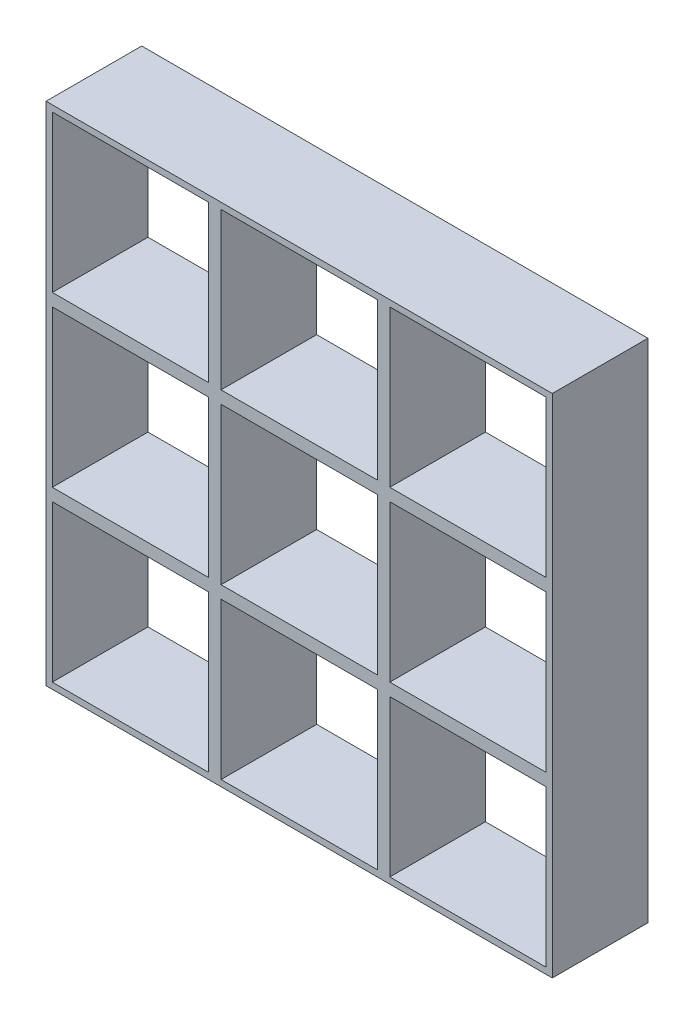
SolidWorks part; units mm, degrees
material "Acrylic (Medium-high impact)"
ref_plane "Front Plane" through (0, 0, 0) normal (0, 0, 1) x (1, 0, 0)
ref_plane "Top Plane" through (0, 0, 0) normal (0, 1, 0) x (1, 0, 0)
ref_plane "Right Plane" through (0, 0, 0) normal (1, 0, 0) x (0, 0, -1)
sketch "Sketch1" plane through (0, 0, 0) normal (0, 0, 1) x (1, 0, 0)
  line L0 (-497.3379, -371.0922) -> (-497.3379, -871.0922)
  line L1 (-1017.3379, 728.9078) -> (602.6621, 728.9078)
  line L2 (-1017.3379, 728.9078) -> (-1017.3379, -891.0922)
  line L3 (-1017.3379, -891.0922) -> (602.6621, -891.0922)
  line L4 (602.6621, 728.9078) -> (602.6621, -891.0922)
  line L5 (42.6621, -371.0922) -> (42.6621, -871.0922)
  line L6 (-997.3379, 168.9078) -> (-997.3379, -331.0922)
  line L7 (82.6621, 168.9078) -> (582.6621, 168.9078)
  line L8 (-497.3379, 708.9078) -> (-497.3379, 208.9078)
  line L9 (42.6621, 708.9078) -> (42.6621, 208.9078)
  line L10 (-997.3379, 168.9078) -> (-497.3379, 168.9078)
  line L11 (-997.3379, 708.9078) -> (-497.3379, 708.9078)
  line L12 (582.6621, 708.9078) -> (582.6621, 208.9078)
  line L13 (-997.3379, -371.0922) -> (-497.3379, -371.0922)
  line L14 (-997.3379, 708.9078) -> (-997.3379, 208.9078)
  line L15 (-997.3379, -871.0922) -> (-497.3379, -871.0922)
  line L16 (82.6621, 708.9078) -> (82.6621, 208.9078)
  line L17 (-457.3379, 708.9078) -> (-457.3379, 208.9078)
  line L18 (-997.3379, -331.0922) -> (-497.3379, -331.0922)
  line L19 (-997.3379, 208.9078) -> (-497.3379, 208.9078)
  line L20 (-1017.3379, 708.9078) -> (582.6621, 708.9078) construction
  line L21 (-997.3379, 728.9078) -> (-997.3379, -871.0922) construction
  line L22 (-457.3379, -331.0922) -> (42.6621, -331.0922)
  line L23 (-457.3379, 708.9078) -> (42.6621, 708.9078)
  line L24 (82.6621, -331.0922) -> (582.6621, -331.0922)
  line L25 (82.6621, -871.0922) -> (582.6621, -871.0922)
  line L28 (82.6621, 708.9078) -> (582.6621, 708.9078)
  line L30 (-457.3379, 208.9078) -> (42.6621, 208.9078)
  line L31 (582.6621, -371.0922) -> (582.6621, -871.0922)
  line L33 (-457.3379, -371.0922) -> (-457.3379, -871.0922)
  line L34 (-457.3379, 168.9078) -> (42.6621, 168.9078)
  line L35 (-457.3379, -871.0922) -> (42.6621, -871.0922)
  line L36 (-997.3379, -371.0922) -> (-997.3379, -871.0922)
  line L37 (-457.3379, 168.9078) -> (-457.3379, -331.0922)
  line L38 (-497.3379, 168.9078) -> (-497.3379, -331.0922)
  line L39 (-457.3379, -371.0922) -> (42.6621, -371.0922)
  line L40 (82.6621, -371.0922) -> (82.6621, -871.0922)
  line L41 (-997.3379, -871.0922) -> (602.6621, -871.0922) construction
  line L42 (82.6621, 208.9078) -> (582.6621, 208.9078)
  line L44 (82.6621, -371.0922) -> (582.6621, -371.0922)
  line L45 (582.6621, 708.9078) -> (582.6621, -891.0922) construction
  line L46 (582.6621, 168.9078) -> (582.6621, -331.0922)
  line L47 (42.6621, 168.9078) -> (42.6621, -331.0922)
  line L48 (82.6621, 168.9078) -> (82.6621, -331.0922)
  dimension "D1" = 1620
  dimension "D2" = 1620
  dimension "D7" = 20
  dimension "D8" = 20
extrude "Boss-Extrude1" add sketch "Sketch1" along normal blind 300
sketch "Sketch2" plane through (0, 0, 300) normal (0, 0, 1) x (1, 0, 0)
  line L1 (-1017.3379, 728.9078) -> (602.6621, 728.9078)
  line L2 (-1017.3379, 728.9078) -> (-1017.3379, -891.0922)
  line L3 (-1017.3379, -891.0922) -> (602.6621, -891.0922)
  line L4 (602.6621, 728.9078) -> (602.6621, -891.0922)
  line L5 (82.6621, 708.9078) -> (582.6621, 708.9078)
  line L6 (-997.3379, 708.9078) -> (-497.3379, 708.9078)
  line L7 (-997.3379, 708.9078) -> (-997.3379, 208.9078)
  line L8 (-997.3379, 208.9078) -> (-497.3379, 208.9078)
  line L9 (-497.3379, 708.9078) -> (-497.3379, 208.9078)
  line L10 (-457.3379, 708.9078) -> (42.6621, 708.9078)
  line L11 (-457.3379, 708.9078) -> (-457.3379, 208.9078)
  line L12 (-457.3379, 208.9078) -> (42.6621, 208.9078)
  line L13 (42.6621, 708.9078) -> (42.6621, 208.9078)
  line L14 (82.6621, 708.9078) -> (82.6621, 208.9078)
  line L15 (82.6621, 208.9078) -> (582.6621, 208.9078)
  line L16 (582.6621, 708.9078) -> (582.6621, 208.9078)
  line L18 (-997.3379, 168.9078) -> (-497.3379, 168.9078)
  line L19 (-997.3379, 168.9078) -> (-997.3379, -331.0922)
  line L20 (-997.3379, -331.0922) -> (-497.3379, -331.0922)
  line L21 (-497.3379, 168.9078) -> (-497.3379, -331.0922)
  line L22 (-457.3379, 168.9078) -> (42.6621, 168.9078)
  line L23 (-457.3379, 168.9078) -> (-457.3379, -331.0922)
  line L24 (-457.3379, -331.0922) -> (42.6621, -331.0922)
  line L25 (42.6621, 168.9078) -> (42.6621, -331.0922)
  line L26 (82.6621, 168.9078) -> (582.6621, 168.9078)
  line L27 (82.6621, 168.9078) -> (82.6621, -331.0922)
  line L28 (82.6621, -331.0922) -> (582.6621, -331.0922)
  line L29 (582.6621, 168.9078) -> (582.6621, -331.0922)
  line L33 (-997.3379, -371.0922) -> (-497.3379, -371.0922)
  line L34 (-997.3379, -371.0922) -> (-997.3379, -871.0922)
  line L35 (-997.3379, -871.0922) -> (-497.3379, -871.0922)
  line L36 (-497.3379, -371.0922) -> (-497.3379, -871.0922)
  line L37 (-457.3379, -371.0922) -> (42.6621, -371.0922)
  line L38 (-457.3379, -371.0922) -> (-457.3379, -871.0922)
  line L39 (-457.3379, -871.0922) -> (42.6621, -871.0922)
  line L40 (42.6621, -371.0922) -> (42.6621, -871.0922)
  line L42 (82.6621, -371.0922) -> (582.6621, -371.0922)
  line L43 (82.6621, -371.0922) -> (82.6621, -871.0922)
  line L44 (82.6621, -871.0922) -> (582.6621, -871.0922)
  line L45 (582.6621, -371.0922) -> (582.6621, -871.0922)
extrude "Boss-Extrude2" add sketch "Sketch2" along normal blind 3
sketch "Sketch3" plane through (0, 0, 0) normal (0, 0, -1) x (-1, 0, 0)
  line L0 (997.3379, -871.0922) -> (497.3379, -871.0922) construction
  line L1 (-602.6621, 728.9078) -> (1017.3379, 728.9078)
  line L2 (-602.6621, 728.9078) -> (-602.6621, -891.0922)
  line L3 (-602.6621, -891.0922) -> (1017.3379, -891.0922)
  line L4 (1017.3379, 728.9078) -> (1017.3379, -891.0922)
  line L5 (497.3379, -371.0922) -> (997.3379, -371.0922)
  line L6 (497.3379, -371.0922) -> (497.3379, -871.0922)
  line L7 (497.3379, -871.0922) -> (997.3379, -871.0922)
  line L8 (997.3379, -371.0922) -> (997.3379, -871.0922)
  line L9 (997.3379, -371.0922) -> (997.3379, -871.0922) construction
  line L11 (457.3379, -871.0922) -> (-42.6621, -871.0922)
  line L12 (457.3379, -871.0922) -> (457.3379, -371.0922)
  line L13 (457.3379, -371.0922) -> (-42.6621, -371.0922)
  line L14 (-42.6621, -871.0922) -> (-42.6621, -371.0922)
  line L15 (-82.6621, -371.0922) -> (-582.6621, -371.0922)
  line L16 (-82.6621, -371.0922) -> (-82.6621, -871.0922)
  line L17 (-82.6621, -871.0922) -> (-582.6621, -871.0922)
  line L18 (-582.6621, -371.0922) -> (-582.6621, -871.0922)
  line L19 (-42.6621, 168.9078) -> (457.3379, 168.9078)
  line L20 (-582.6621, -331.0922) -> (-82.6621, -331.0922)
  line L21 (-582.6621, -331.0922) -> (-582.6621, 168.9078)
  line L22 (-582.6621, 168.9078) -> (-82.6621, 168.9078)
  line L23 (-82.6621, -331.0922) -> (-82.6621, 168.9078)
  line L24 (-42.6621, 168.9078) -> (-42.6621, -331.0922)
  line L25 (-42.6621, -331.0922) -> (457.3379, -331.0922)
  line L26 (457.3379, 168.9078) -> (457.3379, -331.0922)
  line L27 (457.3379, 708.9078) -> (-42.6621, 708.9078)
  line L28 (497.3379, -331.0922) -> (997.3379, -331.0922)
  line L29 (497.3379, -331.0922) -> (497.3379, 168.9078)
  line L30 (497.3379, 168.9078) -> (997.3379, 168.9078)
  line L31 (997.3379, -331.0922) -> (997.3379, 168.9078)
  line L32 (997.3379, 208.9078) -> (497.3379, 208.9078)
  line L33 (997.3379, 208.9078) -> (997.3379, 708.9078)
  line L34 (997.3379, 708.9078) -> (497.3379, 708.9078)
  line L35 (497.3379, 208.9078) -> (497.3379, 708.9078)
  line L36 (457.3379, 708.9078) -> (457.3379, 208.9078)
  line L37 (457.3379, 208.9078) -> (-42.6621, 208.9078)
  line L38 (-42.6621, 708.9078) -> (-42.6621, 208.9078)
  line L39 (-82.6621, 208.9078) -> (-582.6621, 208.9078)
  line L40 (-82.6621, 208.9078) -> (-82.6621, 708.9078)
  line L41 (-82.6621, 708.9078) -> (-582.6621, 708.9078)
  line L42 (-582.6621, 208.9078) -> (-582.6621, 708.9078)
extrude "Boss-Extrude3" add sketch "Sketch3" along normal blind 3
